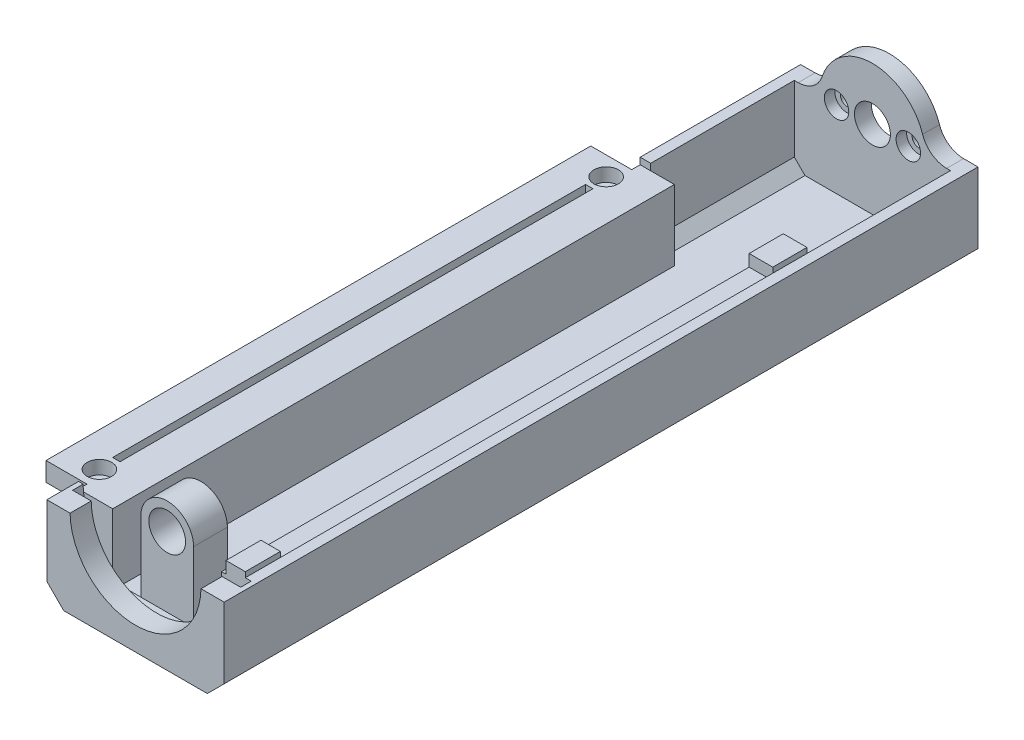
SolidWorks part; units mm, degrees
ref_plane "Front Plane" through (0, 0, 0) normal (0, 0, 1) x (1, 0, 0)
ref_plane "Top Plane" through (0, 0, 0) normal (0, 1, 0) x (1, 0, 0)
ref_plane "Right Plane" through (0, 0, 0) normal (1, 0, 0) x (0, 0, -1)
sketch "Sketch1" plane through (0, 0, 0) normal (0, 0, 1) x (1, 0, 0)
  line L0 (-21, -0.25) -> (21, -0.25)
  line L1 (-21, 21) -> (21, 21) construction
  line L2 (-21, 21) -> (-21, -21) construction
  line L3 (-21, -21) -> (21, -21) construction
  line L4 (21, 21) -> (21, -21) construction
  line L5 (-21, 21) -> (21, -21) construction
  line L6 (-21, -21) -> (21, 21) construction
  line L7 (21, -0.25) -> (21, -17)
  line L8 (21, -17) -> (17, -21)
  line L9 (17, -21) -> (-17, -21)
  line L10 (-17, -21) -> (-21, -17)
  line L11 (-21, -17) -> (-21, -0.25)
  point P0 (0, 0)
  dimension "D1" = 42
  dimension "D2" = 0.25
  dimension "D3" = 4
  dimension "D4" = 4
  dimension "D5" = 4
extrude "Boss-Extrude1" add sketch "Sketch1" along normal blind 178.5 contours L11 L0 L7 L8 L9 L10
ref_plane "Plane1" through (0, 0, 173.5) normal (0, 0, 1) x (1, 0, 0)
sketch "Sketch4" plane through (0, 0, 173.5) normal (0, 0, 1) x (1, 0, 0)
  line L6 (-18.5, -15.9645) -> (-15.9645, -18.5)
  line L7 (-15.9645, -18.5) -> (15.9645, -18.5)
  line L8 (15.9645, -18.5) -> (18.5, -15.9645)
  line L9 (18.5, -15.9645) -> (18.5, -2.75)
  line L11 (-18.5, -2.75) -> (-18.5, -15.9645)
  line L18 (-21, -17) -> (-17, -21)
  line L22 (-21, -0.25) -> (-21, -17)
  line L23 (21, -0.25) -> (-21, -0.25)
  line L24 (21, -17) -> (21, -0.25)
  line L25 (17, -21) -> (21, -17)
  line L26 (-17, -21) -> (17, -21)
  line L27 (-21, -17) -> (-17, -21) construction
  line L28 (-21, -0.25) -> (-21, -17) construction
  line L29 (21, -0.25) -> (-21, -0.25) construction
  line L30 (21, -17) -> (21, -0.25) construction
  line L31 (17, -21) -> (21, -17) construction
  line L32 (-17, -21) -> (17, -21) construction
  line L33 (-18.5, -2.75) -> (-18.5, -0.25)
  line L34 (-18.5, -0.25) -> (18.5, -0.25)
  line L35 (18.5, -0.25) -> (18.5, -2.75)
  line L39 (18.5, -2.75) -> (-18.5, -2.75) construction
  dimension "D1" = 0
  dimension "D2" = 2.5
extrude "Cut-Extrude3" cut sketch "Sketch4" against normal offset from surface (169.5 mm away) 4 up to face at (0, -12.75, 0)
sketch "Sketch3" plane through (0, 0, 178.5) normal (0, 0, 1) x (1, 0, 0)
  circle A0 centre (0, 0) radius 15.5
  dimension "D1" = 31
extrude "Cut-Extrude2" cut sketch "Sketch3" against normal up to next
sketch "Sketch6" plane through (0, 0, 173.5) normal (0, 0, 1) x (1, 0, 0)
  line L1 (-16.6, 16.6) -> (16.6, 16.6) construction
  line L2 (-16.6, 16.6) -> (-16.6, -16.6) construction
  line L3 (-16.6, -16.6) -> (16.6, -16.6) construction
  line L4 (16.6, 16.6) -> (16.6, -16.6) construction
  line L5 (-16.6, 16.6) -> (16.6, -16.6) construction
  line L6 (-16.6, -16.6) -> (16.6, 16.6) construction
  line L8 (-10.975, 16.6) -> (10.975, 16.6)
  line L9 (0, 0) -> (0, 16.6) construction
  line L20 (10.975, -16.6) -> (-10.975, -16.6)
  arc A13 (-10.975, 16.6) -> (-10.975, -16.6) centre (0, 0) ccw
  arc A14 (10.975, -16.6) -> (10.975, 16.6) centre (0, 0) ccw
  point P0 (0, 0)
  dimension "D1" = 39.8
  dimension "D2" = 33.2
extrude "Cut-Extrude4" cut sketch "Sketch6" against normal blind 2.5
ref_plane "Plane2" through (0, 0, 171) normal (0, 0, 1) x (1, 0, 0)
sketch "Sketch7" plane through (0, 0, 171) normal (0, 0, 1) x (1, 0, 0)
  line L1 (-6.25, 0) -> (-6.25, -21)
  line L2 (-6.25, -21) -> (6.25, -21)
  line L3 (6.25, -21) -> (6.25, 0)
  line L6 (17, -21) -> (-17, -21) construction
  arc A4 (-6.25, 0) -> (6.25, 0) centre (0, 0) cw
  circle A5 centre (0, 0) radius 4.25
  dimension "D2" = 6.25
  dimension "D1" = 8.5
extrude "Boss-Extrude3" add sketch "Sketch7" against normal blind 8 contours L3 A4 L1 L2
sketch "Sketch10" plane through (0, 0, 171) normal (0, 0, 1) x (1, 0, 0)
  line L0 (-18.5, -1.8) -> (-18.5, -15.9645)
  line L2 (-18.5, -15.9645) -> (-15.9645, -18.5)
  line L3 (-15.9645, -18.5) -> (-12.9, -18.5)
  line L5 (-12.9, -18.5) -> (-12.9, -1.8)
  line L6 (-18.5, -1.8) -> (-12.9, -1.8)
  dimension "D2" = 0.5
extrude "Boss-Extrude4" add sketch "Sketch10" against normal blind 133 contours L6 L5 L3 L2 L0
mirror "Mirror1" about plane through (0, 0, 0) normal (1, 0, 0) of "Boss-Extrude4"
sketch "Sketch11" plane through (0, 0, 171) normal (0, 0, 1) x (1, 0, 0)
  circle A0 centre (0, 0) radius 4.35
  dimension "D1" = 8.7
extrude "Cut-Extrude6" cut sketch "Sketch11" against normal blind 10
sketch "Sketch12" plane through (0, 0, 38) normal (0, 0, -1) x (-1, 0, 0)
  line L1 (18.5, -1.8) -> (25.3381, -1.8)
  line L2 (18.5, -1.8) -> (18.5, 0)
  line L3 (18.5, 0) -> (25.3381, 0)
  line L4 (25.3381, -1.8) -> (25.3381, 0)
extrude "Cut-Extrude7" cut sketch "Sketch12" against normal up to vertex (133 mm away)
sketch "Sketch13" plane through (0, -1.8, 0) normal (0, 1, 0) x (1, 0, 0)
  line L0 (-18.5, -38) -> (-12.9, -38) construction
  line L1 (-12.9, -40) -> (-30.7, -40)
  line L2 (-12.9, -40) -> (-12.9, -169)
  line L3 (-12.9, -169) -> (-30.7, -169)
  line L4 (-30.7, -40) -> (-30.7, -169)
  line L5 (-12.9, -38) -> (-12.9, -171) construction
  dimension "D1" = 129
  dimension "D2" = 17.8
  dimension "D3" = 2
extrude "Boss-Extrude5" add sketch "Sketch13" against normal blind 4.5
sketch "Sketch16" plane through (0, -6.3, 0) normal (0, -1, 0) x (1, 0, 0)
  line L2 (-30.7, 169) -> (-21, 169) construction
  line L3 (-30.7, 40) -> (-14.4, 40)
  line L4 (-30.7, 40) -> (-30.7, 169)
  line L5 (-30.7, 169) -> (-14.4, 169)
  line L6 (-14.4, 40) -> (-14.4, 169)
  dimension "D1" = 16.3
extrude "Cut-Extrude8" cut sketch "Sketch16" along normal through all
sketch "Sketch17" plane through (0, -6.3, 0) normal (0, -1, 0) x (1, 0, 0)
  line L0 (-22.55, 40) -> (-22.55, 169) construction
  line L1 (-30.7, 40) -> (-14.4, 40) construction
  line L2 (-30.7, 169) -> (-21, 169) construction
  line L3 (-22.55, 104.5) -> (-30.7, 104.5) construction
  line L4 (-21.675, 48.5) -> (-23.425, 48.5)
  line L5 (-21.675, 48.5) -> (-21.675, 160.5)
  line L6 (-21.675, 160.5) -> (-23.425, 160.5)
  line L7 (-23.425, 48.5) -> (-23.425, 160.5)
  line L8 (-21.675, 48.5) -> (-23.425, 160.5) construction
  line L9 (-21.675, 160.5) -> (-23.425, 48.5) construction
  line L10 (-30.7, 40) -> (-30.7, 169) construction
  circle A0 centre (-22.55, 164.5) radius 1.6
  circle A1 centre (-22.55, 44.5) radius 1.6
  point P7 (-22.55, 104.5)
  point P8 (-22.55, 40)
  dimension "D3" = 3.2
  dimension "D1" = 112
  dimension "D2" = 1.75
  dimension "D4" = 60
extrude "Cut-Extrude10" cut sketch "Sketch17" against normal through all
sketch "Sketch18" plane through (0, -1.8, 0) normal (0, 1, 0) x (1, 0, 0)
  circle A0 centre (-22.55, -164.5) radius 2.9
  circle A1 centre (-22.55, -44.5) radius 2.9
  dimension "D1" = 5.8
extrude "Cut-Extrude11" cut sketch "Sketch18" against normal blind 3.2
sketch "Sketch19" plane through (0, 0, 0) normal (0, 0, 1) x (1, 0, 0)
  circle A0 centre (0, 0) radius 12.5
  dimension "D1" = 25
extrude "Boss-Extrude6" add sketch "Sketch19" along normal blind 4 contours A0
sketch "Sketch20" plane through (0, 0, 0) normal (0, 0, 1) x (1, 0, 0)
  line L0 (-21, 21) -> (21, -21) construction
  line L1 (-21, -0.25) -> (21, -0.25) construction
  line L2 (0, 0) -> (0, 12.5) construction
  circle A0 centre (0, 0) radius 4.25
  circle A1 centre (-8.5, -0.25) radius 1.6
  arc A2 (12.4975, -0.25) -> (-12.4975, -0.25) centre (0, 0) ccw construction
  circle A3 centre (8.5, -0.25) radius 1.6
  dimension "D1" = 8.5
  dimension "D2" = 3.2
  dimension "D3" = 8.5
extrude "Cut-Extrude12" cut sketch "Sketch20" along normal blind 4
sketch "Sketch21" plane through (0, 0, 4) normal (0, 0, 1) x (1, 0, 0)
  circle A0 centre (-8.5, -0.25) radius 2.9
  circle A1 centre (8.5, -0.25) radius 2.9
  dimension "D1" = 5.8
extrude "Cut-Extrude13" cut sketch "Sketch21" against normal blind 2.5
fillet "Fillet1" radius 6 2 edges at (12.4975, -0.25, 2) (-12.4975, -0.25, 2)
sketch "Sketch22" plane through (0, -1.8, 0) normal (0, 1, 0) x (1, 0, 0)
  line L0 (18.5, -38) -> (18.5, -171) construction
  line L1 (12.9, -38) -> (18.5, -38)
  line L2 (12.9, -38) -> (12.9, -46.1)
  line L3 (12.9, -46.1) -> (18.5, -46.1)
  line L4 (18.5, -38) -> (18.5, -46.1)
  line L5 (18.5, -171) -> (12.9, -171) construction
  line L6 (18.5, -171) -> (13.9, -171)
  line L7 (18.5, -171) -> (18.5, -162.7)
  line L8 (18.5, -162.7) -> (13.9, -162.7)
  line L9 (13.9, -171) -> (13.9, -162.7)
  line L10 (12.9, -38) -> (12.9, -171) construction
  dimension "D1" = 8.1
  dimension "D2" = 1
  dimension "D3" = 8.3
extrude "Boss-Extrude7" add sketch "Sketch22" along normal blind 2.8
sketch "Sketch23" plane through (0, 0, 173.5) normal (0, 0, -1) x (-1, 0, 0)
  line L0 (-10.975, -16.6) -> (10.975, -16.6) construction
  line L1 (-10.975, -16.6) -> (10.975, -16.6)
  line L2 (18.5, -7.3321) -> (-18.5, -7.3321) construction
  line L4 (-18.5, -15.9645) -> (-18.5, -7.3321) construction
  line L5 (-15.9645, -18.5) -> (-18.5, -15.9645) construction
  line L6 (15.9645, -18.5) -> (-15.9645, -18.5) construction
  line L7 (18.5, -15.9645) -> (15.9645, -18.5) construction
  line L8 (18.5, -7.3321) -> (18.5, -15.9645) construction
  line L9 (-18.5, -15.9645) -> (-18.5, -7.3321)
  line L10 (-15.9645, -18.5) -> (-18.5, -15.9645)
  line L11 (15.9645, -18.5) -> (-15.9645, -18.5)
  line L12 (18.5, -15.9645) -> (15.9645, -18.5)
  line L13 (18.5, -7.3321) -> (18.5, -15.9645)
  arc A0 (-10.975, 16.6) -> (-10.975, -16.6) centre (0, 0) ccw construction
  arc A1 (10.975, -16.6) -> (10.975, 16.6) centre (0, 0) ccw construction
  arc A2 (-18.5, -7.3321) -> (-10.975, -16.6) centre (0, 0) ccw
  arc A3 (10.975, -16.6) -> (18.5, -7.3321) centre (0, 0) ccw
extrude "Boss-Extrude8" add sketch "Sketch23" along normal up to surface (2.5 mm away)
